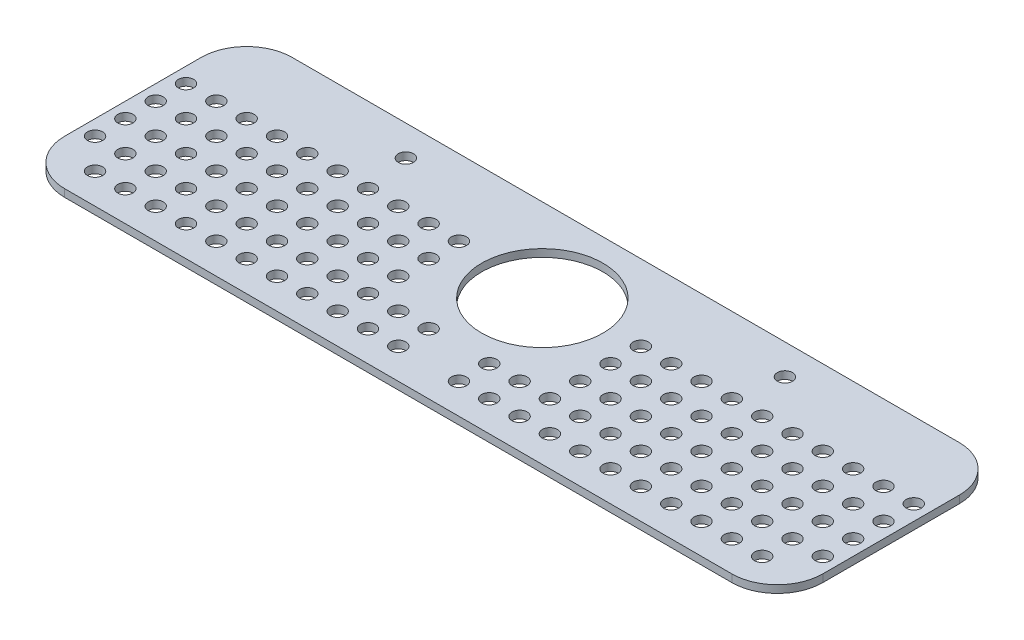
SolidWorks part; units mm, degrees
ref_plane "Front Plane" through (0, 0, 0) normal (0, 0, 1) x (1, 0, 0)
ref_plane "Top Plane" through (0, 0, 0) normal (0, 1, 0) x (1, 0, 0)
ref_plane "Right Plane" through (0, 0, 0) normal (1, 0, 0) x (0, 0, -1)
sketch "Sketch1" plane through (0, 0, 0) normal (0, 1, 0) x (1, 0, 0)
  line L0 (-415.0151, 97.0124) -> (383.6515, 97.0124) construction
  line L1 (220, -75) -> (-220, -75)
  line L2 (250, -45) -> (250, 45)
  line L3 (220, 75) -> (-220, 75)
  line L4 (-250, -45) -> (-250, 45)
  line L5 (250, -75) -> (-250, 75) construction
  line L6 (250, 75) -> (-250, -75) construction
  line L7 (0, -75) -> (0, 75) construction
  line L12 (-285.1751, 35) -> (357.6933, 35) construction
  line L13 (-285.1751, -65) -> (357.6933, -65) construction
  line L14 (-240, 25) -> (-220, 25) construction
  arc A0 (250, 45) -> (220, 75) centre (220, 45) ccw
  arc A1 (250, -45) -> (220, -75) centre (220, -45) cw
  arc A2 (-220, -75) -> (-250, -45) centre (-220, -45) cw
  arc A3 (-250, 45) -> (-220, 75) centre (-220, 45) cw
  circle A8 centre (0, 20) radius 40
  circle A25 centre (-125, 55) radius 5
  circle A26 centre (125, 55) radius 5
  circle A27 centre (0, 20) radius 30 construction
  circle A28 centre (-240, 25) radius 10 construction
  circle A29 centre (-240, 25) radius 5
  circle A30 centre (-220, 25) radius 5
  circle A31 centre (-200, 25) radius 5
  circle A32 centre (-180, 25) radius 5
  circle A33 centre (-160, 25) radius 5
  circle A34 centre (-140, 25) radius 5
  circle A35 centre (-120, 25) radius 5
  circle A36 centre (-100, 25) radius 5
  circle A37 centre (-80, 25) radius 5
  circle A38 centre (-60, 25) radius 5
  circle A39 centre (-240, 5) radius 5
  circle A40 centre (-220, 5) radius 5
  circle A41 centre (-200, 5) radius 5
  circle A42 centre (-180, 5) radius 5
  circle A43 centre (-160, 5) radius 5
  circle A44 centre (-140, 5) radius 5
  circle A45 centre (-120, 5) radius 5
  circle A46 centre (-100, 5) radius 5
  circle A47 centre (-80, 5) radius 5
  circle A48 centre (-60, 5) radius 5
  circle A49 centre (-240, -15) radius 5
  circle A50 centre (-220, -15) radius 5
  circle A51 centre (-200, -15) radius 5
  circle A52 centre (-180, -15) radius 5
  circle A53 centre (-160, -15) radius 5
  circle A54 centre (-140, -15) radius 5
  circle A55 centre (-120, -15) radius 5
  circle A56 centre (-100, -15) radius 5
  circle A57 centre (-80, -15) radius 5
  circle A58 centre (-60, -15) radius 5
  circle A59 centre (-240, -35) radius 5
  circle A60 centre (-220, -35) radius 5
  circle A61 centre (-200, -35) radius 5
  circle A62 centre (-180, -35) radius 5
  circle A63 centre (-160, -35) radius 5
  circle A64 centre (-140, -35) radius 5
  circle A65 centre (-120, -35) radius 5
  circle A66 centre (-100, -35) radius 5
  circle A67 centre (-80, -35) radius 5
  circle A68 centre (-60, -35) radius 5
  circle A70 centre (-220, -55) radius 5
  circle A71 centre (-200, -55) radius 5
  circle A72 centre (-180, -55) radius 5
  circle A73 centre (-160, -55) radius 5
  circle A74 centre (-140, -55) radius 5
  circle A75 centre (-120, -55) radius 5
  circle A76 centre (-100, -55) radius 5
  circle A77 centre (-80, -55) radius 5
  circle A78 centre (-60, -55) radius 5
  circle A79 centre (-240, -55) radius 5 [skipped]
  circle A80 centre (-40, -35) radius 5
  circle A81 centre (-40, -55) radius 5
  circle A82 centre (-20, -35) radius 5
  circle A83 centre (-20, -55) radius 5
  circle A84 centre (20, -55) radius 5
  circle A85 centre (40, -55) radius 5
  circle A86 centre (60, -55) radius 5
  circle A87 centre (80, -55) radius 5
  circle A88 centre (100, -55) radius 5
  circle A89 centre (120, -55) radius 5
  circle A90 centre (140, -55) radius 5
  circle A91 centre (120, -35) radius 5
  circle A92 centre (100, -35) radius 5
  circle A93 centre (80, -35) radius 5
  circle A94 centre (60, -35) radius 5
  circle A95 centre (20, -35) radius 5
  circle A96 centre (40, -35) radius 5
  circle A97 centre (60, -15) radius 5
  circle A98 centre (80, -15) radius 5
  circle A99 centre (100, -15) radius 5
  circle A100 centre (120, -15) radius 5
  circle A101 centre (120, 5) radius 5
  circle A102 centre (100, 5) radius 5
  circle A103 centre (80, 5) radius 5
  circle A104 centre (60, 5) radius 5
  circle A105 centre (60, 25) radius 5
  circle A106 centre (80, 25) radius 5
  circle A107 centre (100, 25) radius 5
  circle A108 centre (120, 25) radius 5
  circle A109 centre (140, 25) radius 5
  circle A110 centre (140, 5) radius 5
  circle A111 centre (140, -15) radius 5
  circle A112 centre (140, -35) radius 5
  circle A113 centre (160, -55) radius 5
  circle A114 centre (160, 5) radius 5
  circle A115 centre (160, -15) radius 5
  circle A116 centre (160, -35) radius 5
  circle A117 centre (180, -55) radius 5
  circle A118 centre (180, -35) radius 5
  circle A119 centre (180, -15) radius 5
  circle A120 centre (180, 5) radius 5
  circle A121 centre (160, 25) radius 5
  circle A122 centre (180, 25) radius 5
  circle A123 centre (200, -55) radius 5
  circle A124 centre (200, -15) radius 5
  circle A125 centre (200, -35) radius 5
  circle A126 centre (220, -55) radius 5
  circle A127 centre (220, -35) radius 5
  circle A128 centre (220, -15) radius 5
  circle A129 centre (240, -35) radius 5
  circle A130 centre (240, -15) radius 5
  circle A131 centre (240, 5) radius 5
  circle A132 centre (220, 5) radius 5
  circle A133 centre (200, 5) radius 5
  circle A134 centre (200, 25) radius 5
  circle A135 centre (220, 25) radius 5
  circle A136 centre (240, 25) radius 5
  point P0 (0, 0)
  point P29 (0, 50)
  point P33 (-250, 25)
  point P35 (-240, 35)
  dimension "D3" = 30
  dimension "D4" = 40
  dimension "D5" = 80
  dimension "D8" = 125
  dimension "D9" = 30
  dimension "D10" = 25
  dimension "D11" = 10
  dimension "D12" = 20
  dimension "D6" = 10
  dimension "D7" = 20
  dimension "D15" = 60
  dimension "D18" = 20
  dimension "D19" = 10
  dimension "D1" = 500
  dimension "D2" = 150
  dimension "D13" = 125
  dimension "D14" = 10
  dimension "D16" = 100
  dimension "D17" = 250
  dimension "D21" = 20
  dimension "D20" = 10
  dimension "D22" = 5
  dimension "D23" = 3
extrude "Boss-Extrude1" add sketch "Sketch1" along normal blind 5
